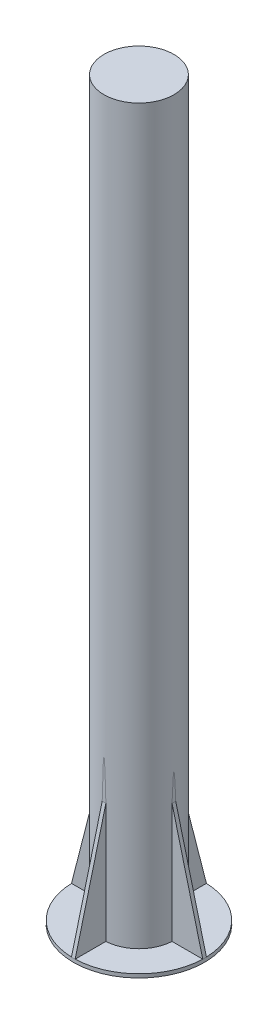
SolidWorks part; units mm, degrees
ref_plane "Front Plane" through (0, 0, 0) normal (0, 0, 1) x (1, 0, 0)
ref_plane "Top Plane" through (0, 0, 0) normal (0, 1, 0) x (1, 0, 0)
ref_plane "Right Plane" through (0, 0, 0) normal (1, 0, 0) x (0, 0, -1)
sketch "Sketch1" plane through (0, 0, 0) normal (0, 1, 0) x (1, 0, 0)
  circle A0 centre (0, 0) radius 107
  dimension "D1" = 214
extrude "Boss-Extrude1" add sketch "Sketch1" along normal blind 6
sketch "Sketch2" plane through (0, 6, 0) normal (0, 1, 0) x (1, 0, 0)
  circle A0 centre (0, 0) radius 57
  dimension "D1" = 114
extrude "Boss-Extrude2" add sketch "Sketch2" along normal blind 1194
sketch "Sketch3" plane through (0, 6, 0) normal (0, 1, 0) x (1, 0, 0)
  line L0 (0, 0) -> (-107, 0) construction
  line L1 (-107, 0) -> (-107, -3)
  line L2 (-107, -3) -> (-3, -3)
  line L3 (107, -3) -> (107, 3)
  line L4 (107, 3) -> (3, 3)
  line L5 (-107, 3) -> (-107, 0)
  line L6 (0, -107) -> (0, 0) construction
  line L7 (0, 0) -> (0, 107) construction
  line L8 (0, 107) -> (-3, 107)
  line L9 (-3, 107) -> (-3, 3)
  line L10 (-3, -107) -> (3, -107)
  line L11 (3, -107) -> (3, -3)
  line L12 (3, 107) -> (0, 107)
  line L13 (-3, -3) -> (-3, -107)
  line L14 (3, -3) -> (107, -3)
  line L16 (3, 3) -> (3, 107)
  line L17 (-3, 3) -> (-107, 3)
  circle A0 centre (0, 0) radius 107 construction
  point P14 (0, 0)
  dimension "D1" = 3
  dimension "D2" = 3
  dimension "D3" = 3
  dimension "D4" = 3
  dimension "D5" = 104
  dimension "D6" = 104
extrude "Boss-Extrude3" add sketch "Sketch3" along normal blind 195
sketch "Sketch4" plane through (0, 0, 3) normal (0, 0, 1) x (1, 0, 0)
  line L0 (-56.921, 201) -> (-107, 6)
  line L1 (-107, 6) -> (-153.8435, 6)
  line L2 (-153.8435, 6) -> (-153.8435, 243.9501)
  line L3 (-153.8435, 243.9501) -> (-57, 243.9501)
  line L4 (-57, 1200) -> (-57, 201) construction
  line L5 (-57, 243.9501) -> (-56.921, 201)
  line L6 (107, 6) -> (56.921, 201)
  line L7 (56.921, 201) -> (57, 243.9501)
  line L8 (57, 201) -> (57, 1200) construction
  line L9 (57, 243.9501) -> (157.6785, 243.9501)
  line L10 (107, 6) -> (157.6785, 6)
  line L11 (157.6785, 6) -> (157.6785, 243.9501)
extrude "Cut-Extrude1" cut sketch "Sketch4" against normal through all
sketch "Sketch6" plane through (-3, 0, 0) normal (-1, 0, 0) x (0, 0, 1)
  line L0 (-107, 6) -> (-56.921, 201)
  line L1 (-56.921, 201) -> (-57, 265.7996)
  line L2 (-57, 1200) -> (-57, 201) construction
  line L3 (-57, 265.7996) -> (-234.3529, 265.7996)
  line L4 (-234.3529, 265.7996) -> (-234.3529, 6)
  line L5 (-234.3529, 6) -> (-107, 6)
  line L6 (107, 6) -> (56.921, 201)
  line L7 (56.921, 201) -> (57, 265.7996)
  line L8 (57, 201) -> (57, 1200) construction
  line L9 (57, 265.7996) -> (191.4432, 265.7996)
  line L10 (191.4432, 265.7996) -> (191.4432, 6)
  line L11 (191.4432, 6) -> (107, 6)
extrude "Cut-Extrude2" cut sketch "Sketch6" against normal through all
